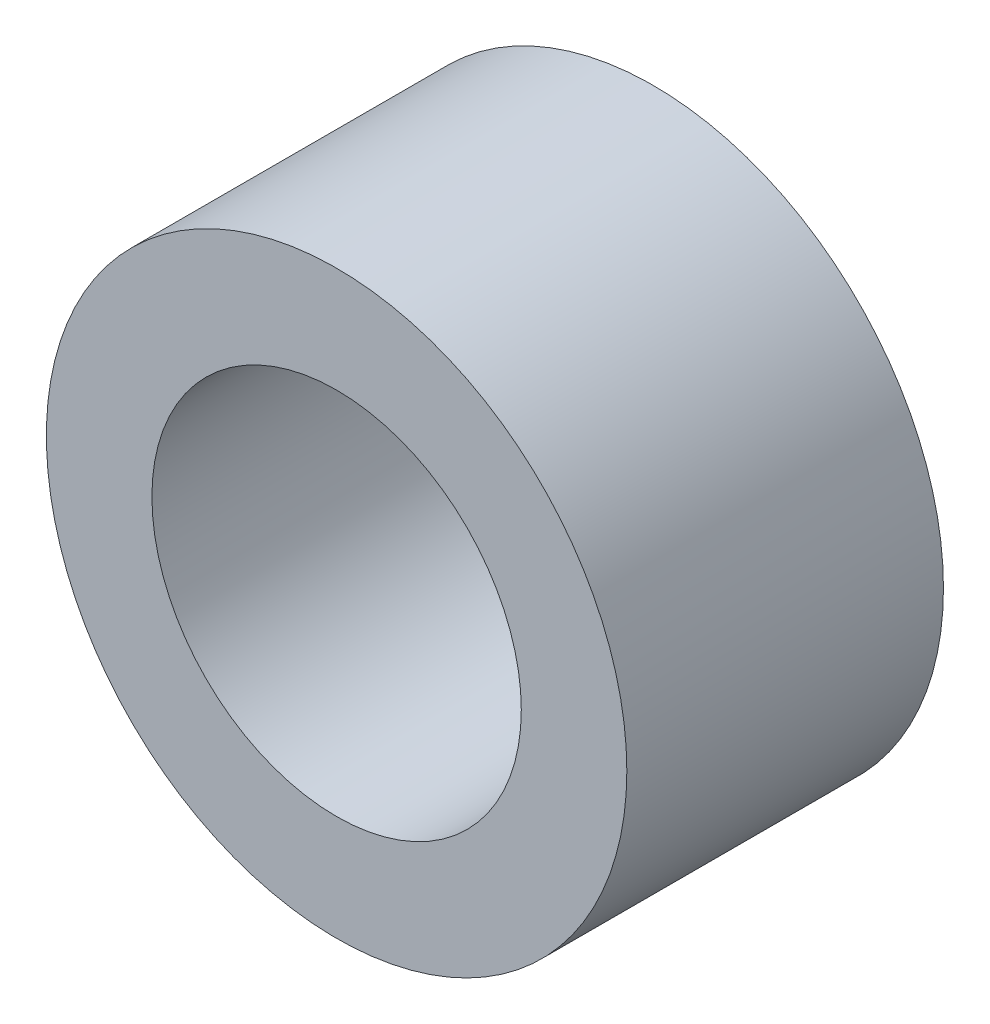
SolidWorks part; units mm, degrees
material "ABS"
ref_plane "前视基准面" through (0, 0, 0) normal (0, 0, 1) x (1, 0, 0)
ref_plane "上视基准面" through (0, 0, 0) normal (0, 1, 0) x (1, 0, 0)
ref_plane "右视基准面" through (0, 0, 0) normal (1, 0, 0) x (0, 0, -1)
sketch "草图1" plane through (0, 0, 0) normal (0, 0, 1) x (1, 0, 0)
  circle A0 centre (0, 0) radius 2.75
  circle A1 centre (0, 0) radius 1.75
  dimension "D1" = 3.5
  dimension "D2" = 5.5
extrude "凸台-拉伸1" add sketch "草图1" along normal blind 3
